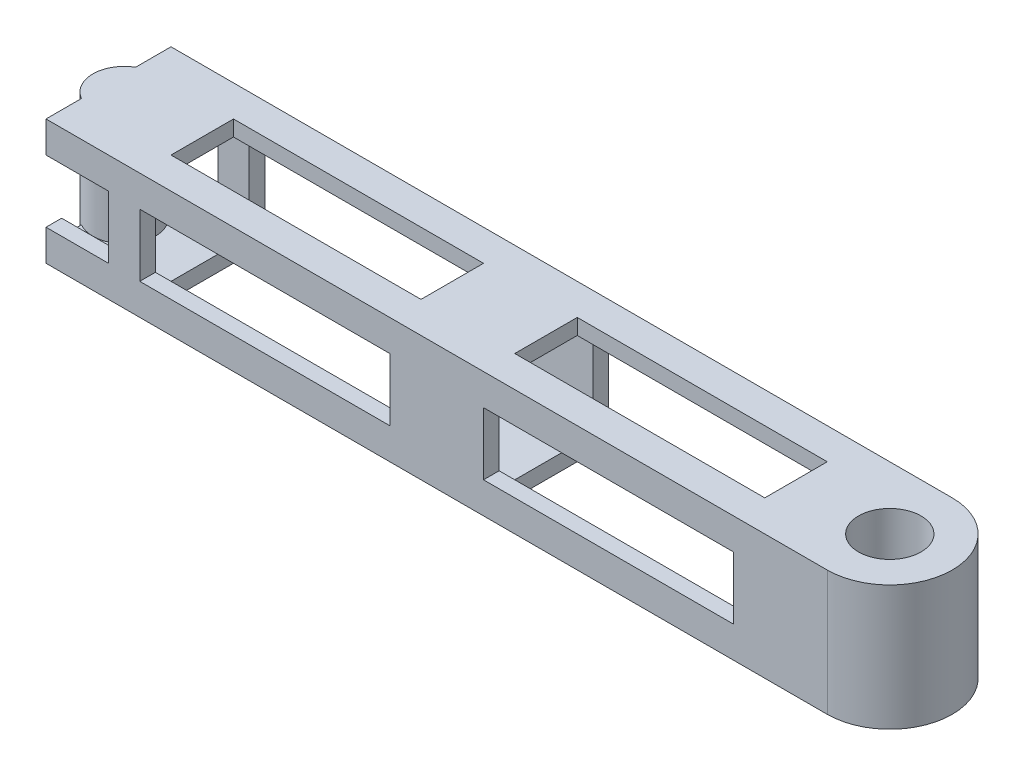
SolidWorks part; units mm, degrees
material "ENPH 253 Hardboard"
ref_plane "Front Plane" through (0, 0, 0) normal (0, 0, 1) x (1, 0, 0)
ref_plane "Top Plane" through (0, 0, 0) normal (0, 1, 0) x (1, 0, 0)
ref_plane "Right Plane" through (0, 0, 0) normal (1, 0, 0) x (0, 0, -1)
sketch "Sketch1" plane through (0, 0, 0) normal (0, 0, 1) x (1, 0, 0)
  line L1 (-120.122, -73.9329) -> (129.878, -73.9329)
  line L2 (-120.122, -73.9329) -> (-120.122, -113.9329)
  line L3 (-120.122, -113.9329) -> (129.878, -113.9329)
  line L4 (129.878, -73.9329) -> (129.878, -113.9329)
  dimension "D1" = 40
  dimension "D2" = 250
extrude "Boss-Extrude1" add sketch "Sketch1" along normal blind 40
sketch "Sketch2" plane through (129.878, 0, 0) normal (1, 0, 0) x (0, 0, -1)
  line L0 (-40, -73.9329) -> (0, -73.9329) construction
  line L1 (-35, -78.9329) -> (-5, -78.9329)
  line L2 (-35, -78.9329) -> (-35, -108.9329)
  line L3 (-35, -108.9329) -> (-5, -108.9329)
  line L4 (-5, -78.9329) -> (-5, -108.9329)
  line L5 (-40, -113.9329) -> (-40, -73.9329) construction
  line L6 (0, -113.9329) -> (0, -73.9329) construction
  line L7 (-40, -113.9329) -> (0, -113.9329) construction
  dimension "D1" = 5
  dimension "D2" = 5
  dimension "D3" = 5
  dimension "D4" = 5
extrude "Cut-Extrude1" cut sketch "Sketch2" against normal through all both and the other way through all
sketch "Sketch3" plane through (0, 0, 0) normal (0, 0, -1) x (-1, 0, 0)
  line L0 (-129.878, -73.9329) -> (120.122, -73.9329) construction
  line L1 (-99.878, -83.9329) -> (-19.878, -83.9329)
  line L2 (-99.878, -83.9329) -> (-99.878, -103.9329)
  line L3 (-99.878, -103.9329) -> (-19.878, -103.9329)
  line L4 (-19.878, -83.9329) -> (-19.878, -103.9329)
  line L5 (10.122, -83.9329) -> (90.122, -83.9329)
  line L6 (10.122, -83.9329) -> (10.122, -103.9329)
  line L7 (10.122, -103.9329) -> (90.122, -103.9329)
  line L8 (90.122, -83.9329) -> (90.122, -103.9329)
  line L9 (120.122, -113.9329) -> (-129.878, -113.9329) construction
  line L10 (-129.878, -113.9329) -> (-129.878, -73.9329) construction
  dimension "D1" = 10
  dimension "D2" = 10
  dimension "D3" = 10
  dimension "D4" = 10
  dimension "D5" = 30
  dimension "D6" = 80
  dimension "D7" = 80
  dimension "D8" = 30
extrude "Cut-Extrude2" cut sketch "Sketch3" against normal through all both and the other way through all
sketch "Sketch4" plane through (0, -73.9329, 0) normal (0, 1, 0) x (1, 0, 0)
  line L0 (129.878, 0) -> (-120.122, 0) construction
  line L1 (19.878, -30) -> (99.878, -30)
  line L2 (19.878, -30) -> (19.878, -10)
  line L3 (19.878, -10) -> (99.878, -10)
  line L4 (99.878, -30) -> (99.878, -10)
  line L5 (-90.122, -30) -> (-10.122, -30)
  line L6 (-90.122, -30) -> (-90.122, -10)
  line L7 (-90.122, -10) -> (-10.122, -10)
  line L8 (-10.122, -30) -> (-10.122, -10)
  line L9 (129.878, -40) -> (-120.122, -40) construction
  line L10 (129.878, -40) -> (129.878, 0) construction
  dimension "D1" = 10
  dimension "D2" = 10
  dimension "D3" = 30
  dimension "D4" = 30
  dimension "D5" = 80
  dimension "D6" = 10
  dimension "D7" = 10
  dimension "D8" = 80
extrude "Cut-Extrude3" cut sketch "Sketch4" against normal through all both and the other way through all
sketch "Sketch5" plane through (0, 0, 40) normal (0, 0, 1) x (1, 0, 0)
  line L0 (-120.122, -73.9329) -> (-120.122, -113.9329) construction
  line L1 (-120.122, -83.9329) -> (-100.122, -83.9329)
  line L2 (-120.122, -83.9329) -> (-120.122, -103.9329)
  line L3 (-120.122, -103.9329) -> (-100.122, -103.9329)
  line L4 (-100.122, -83.9329) -> (-100.122, -103.9329)
  line L5 (129.878, -73.9329) -> (-120.122, -73.9329) construction
  line L6 (-120.122, -113.9329) -> (129.878, -113.9329) construction
  line L7 (-90.122, -103.9329) -> (-90.122, -83.9329) construction
  dimension "D1" = 10
  dimension "D2" = 10
  dimension "D3" = 10
extrude "Cut-Extrude4" cut sketch "Sketch5" against normal through all both and the other way through all
sketch "Sketch6" plane through (0, -113.9329, 0) normal (0, -1, 0) x (1, 0, 0)
  line L0 (-120.122, 0) -> (129.878, 0) construction
  line L1 (-120.122, 40) -> (-120.122, 0) construction
  circle A0 centre (-115.122, 20) radius 10
  dimension "D1" = 20
  dimension "D2" = 5
extrude "Boss-Extrude2" add sketch "Sketch6" against normal blind 40
sketch "Sketch7" plane through (0, -113.9329, 0) normal (0, -1, 0) x (1, 0, 0)
  line L0 (129.878, 40) -> (129.878, 0) construction
  circle A0 centre (129.878, 20) radius 20
extrude "Boss-Extrude3" add sketch "Sketch7" against normal blind 40
sketch "Sketch8" plane through (0, -113.9329, 0) normal (0, -1, 0) x (-1, 0, 0)
  circle A0 centre (-129.878, -20) radius 10
  arc A1 (-129.878, 0) -> (-129.878, -40) centre (-129.878, -20) ccw construction
  dimension "D1" = 0
extrude "Cut-Extrude5" cut sketch "Sketch8" against normal through all both and the other way through all
